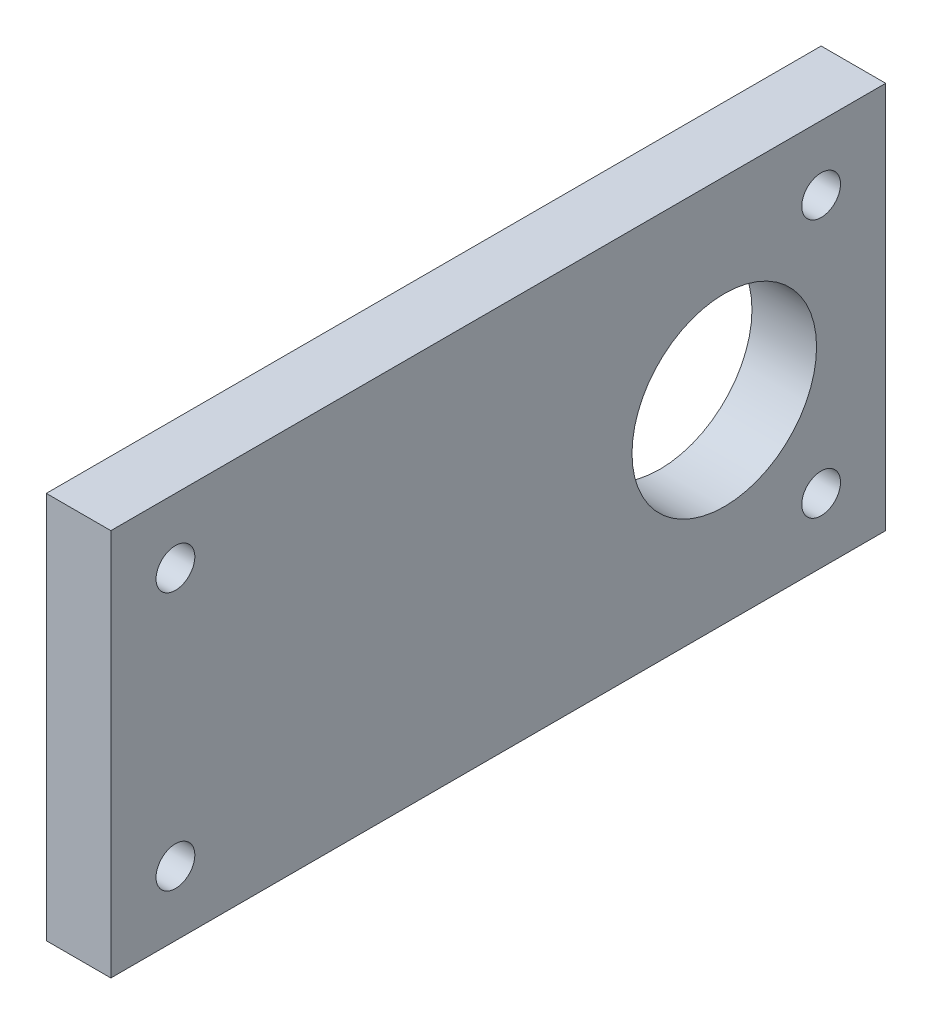
SolidWorks part; units mm, degrees
ref_plane "Alzado" through (0, 0, 0) normal (0, 0, 1) x (1, 0, 0)
ref_plane "Planta" through (0, 0, 0) normal (0, 1, 0) x (1, 0, 0)
ref_plane "Vista lateral" through (0, 0, 0) normal (1, 0, 0) x (0, 0, -1)
sketch "Croquis1" plane through (0, 0, 0) normal (1, 0, 0) x (0, 0, -1)
  line L1 (-80, -30) -> (80, -30)
  line L2 (-80, -30) -> (-80, 30)
  line L3 (-80, 30) -> (80, 30)
  line L4 (80, -30) -> (80, 30)
  line L5 (-80, -30) -> (80, 30) construction
  line L6 (-80, 30) -> (80, -30) construction
  point P0 (0, 0)
  dimension "D1" = 160
  dimension "D2" = 60
extrude "Saliente-Extruir1" add sketch "Croquis1" along normal blind 10
sketch "Croquis2" plane through (0, 0, 0) normal (-1, 0, 0) x (0, 0, 1)
  circle A0 centre (-58.2308, 0) radius 14.29
  circle A1 centre (-15, 0) radius 14.29
  dimension "D1" = 28.58
extrude "Cortar-Extruir1" cut sketch "Croquis2" against normal through all
sketch "Croquis3" plane through (0, 0, 0) normal (-1, 0, 0) x (0, 0, 1)
  line L0 (80, -30) -> (-80, -30) construction
  line L1 (-80, 30) -> (-40, 30)
  line L2 (-80, 30) -> (-80, -30)
  line L3 (-80, -30) -> (-40, -30)
  line L4 (-40, 30) -> (-40, -30)
  dimension "D1" = 40
extrude "Cortar-Extruir2" cut sketch "Croquis3" against normal through all
sketch "Croquis4" plane through (0, 0, 0) normal (-1, 0, 0) x (0, 0, 1)
  line L0 (-40, -30) -> (-40, 30) construction
  line L1 (-40, 30) -> (80, 30) construction
  line L2 (80, -30) -> (-40, -30) construction
  line L3 (80, 30) -> (80, -30) construction
  circle A0 centre (70, 20) radius 3
  circle A1 centre (-30, 20) radius 3
  circle A2 centre (-30, -20) radius 3
  circle A3 centre (70, -20) radius 3
  dimension "D1" = 6
  dimension "D2" = 10
  dimension "D3" = 10
  dimension "D4" = 10
  dimension "D5" = 10
  dimension "D6" = 10
  dimension "D7" = 10
  dimension "D8" = 10
  dimension "D9" = 10
extrude "Cortar-Extruir3" cut sketch "Croquis4" against normal through all
